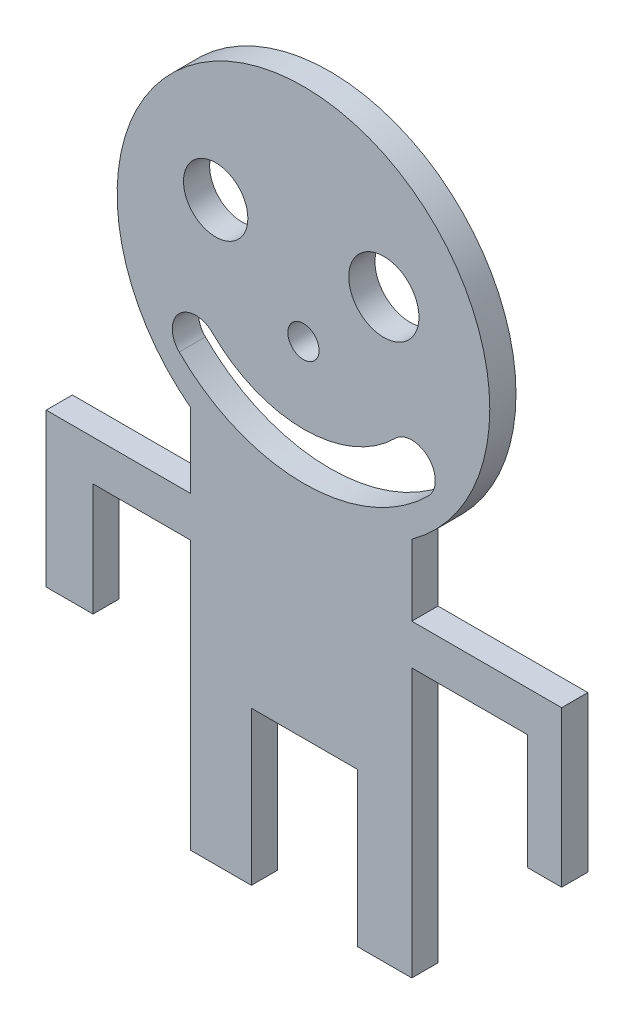
SolidWorks part; units mm, degrees
ref_plane "Front Plane" through (0, 0, 0) normal (0, 0, 1) x (1, 0, 0)
ref_plane "Top Plane" through (0, 0, 0) normal (0, 1, 0) x (1, 0, 0)
ref_plane "Right Plane" through (0, 0, 0) normal (1, 0, 0) x (0, 0, -1)
sketch "Sketch1" plane through (0, 0, 0) normal (0, 0, 1) x (1, 0, 0)
  line L0 (-43.1667, -100.459) -> (-43.1667, -144.3864)
  line L6 (-43.1667, -56.5317) -> (-43.1667, -85.0113)
  line L7 (-19.8961, -144.3864) -> (20.7153, -144.3864)
  line L8 (41.35, -57.8738) -> (41.35, -85.0113)
  line L10 (-43.1667, -144.3864) -> (-43.1667, -202.9776)
  line L11 (-43.1667, -202.9776) -> (-19.8961, -202.9776)
  line L12 (-19.8961, -144.3864) -> (-19.8961, -202.9776)
  line L14 (41.35, -144.3864) -> (41.35, -202.9776)
  line L15 (41.35, -202.9776) -> (20.7153, -202.9776)
  line L16 (20.7153, -144.3864) -> (20.7153, -202.9776)
  line L17 (41.35, -85.0113) -> (98.5537, -85.0113)
  line L19 (41.35, -100.459) -> (85.5, -100.459)
  line L20 (98.5537, -85.0113) -> (98.5537, -100.459)
  line L21 (-43.1667, -85.0113) -> (-98.218, -85.0113)
  line L23 (-43.1667, -100.459) -> (-80.3296, -100.459)
  line L24 (-98.218, -85.0113) -> (-98.218, -100.459)
  line L26 (-98.218, -100.459) -> (-98.218, -143.511)
  line L27 (-98.218, -143.511) -> (-80.3296, -143.511)
  line L28 (-80.3296, -100.459) -> (-80.3296, -143.511)
  line L30 (98.5537, -100.459) -> (98.5537, -144.3864)
  line L31 (98.5537, -144.3864) -> (85.5, -144.3864)
  line L32 (85.5, -100.459) -> (85.5, -144.3864)
  line L33 (41.35, -100.459) -> (41.35, -144.3864)
  arc A0 (41.35, -57.8738) -> (-43.1667, -56.5317) centre (0, 0) ccw
  circle A1 centre (-33.5174, 16.8514) radius 12.288
  circle A2 centre (30.6885, 16.8514) radius 13.4023
  circle A3 centre (0, -13.2378) radius 5.9667
  arc A4 (41.35, -34.0869) -> (-41.0989, -34.0869) centre (0.1255, 7.1376) cw construction
  arc A5 (-47.4425, -40.4304) -> (47.6935, -40.4304) centre (0.1255, 7.1376) ccw
  arc A6 (-34.7554, -27.7434) -> (35.0065, -27.7434) centre (0.1255, 7.1376) ccw
  arc A7 (-34.7554, -27.7434) -> (-47.4425, -40.4304) centre (-41.0989, -34.0869) ccw
  arc A8 (47.6935, -40.4304) -> (35.0065, -27.7434) centre (41.35, -34.0869) ccw
  point P13 (0.1255, -51.1626)
  point P42 (-80.3296, -143.511)
  point P43 (41.35, -57.8738)
extrude "Boss-Extrude1" add sketch "Sketch1" along normal blind 10
